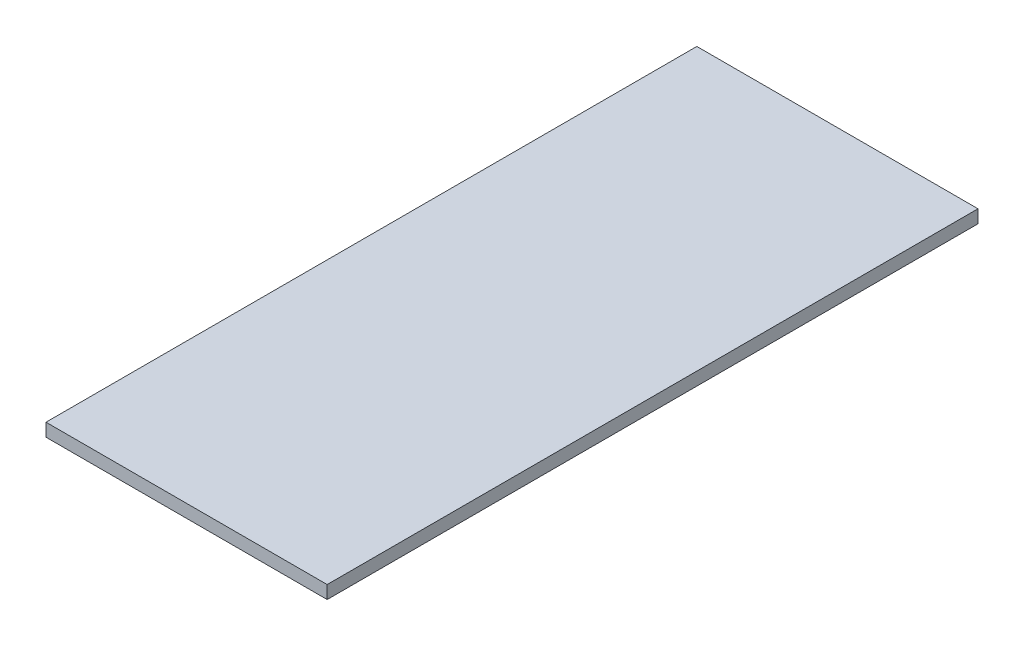
SolidWorks part; units mm, degrees
ref_plane "Plano frontal" through (0, 0, 0) normal (0, 0, 1) x (1, 0, 0)
ref_plane "Plano superior" through (0, 0, 0) normal (0, 1, 0) x (1, 0, 0)
ref_plane "Plano direito" through (0, 0, 0) normal (1, 0, 0) x (0, 0, -1)
sketch "Esboço1" plane through (0, 0, 0) normal (0, 1, 0) x (1, 0, 0)
  line L1 (-10.8, -25) -> (10.8, -25)
  line L2 (-10.8, -25) -> (-10.8, 25)
  line L3 (-10.8, 25) -> (10.8, 25)
  line L4 (10.8, -25) -> (10.8, 25)
  line L5 (-10.8, -25) -> (10.8, 25) construction
  line L6 (-10.8, 25) -> (10.8, -25) construction
  point P0 (0, 0)
  dimension "D1" = 21.6
  dimension "D2" = 50
extrude "Ressalto-extrusão1" add sketch "Esboço1" along normal blind 1
